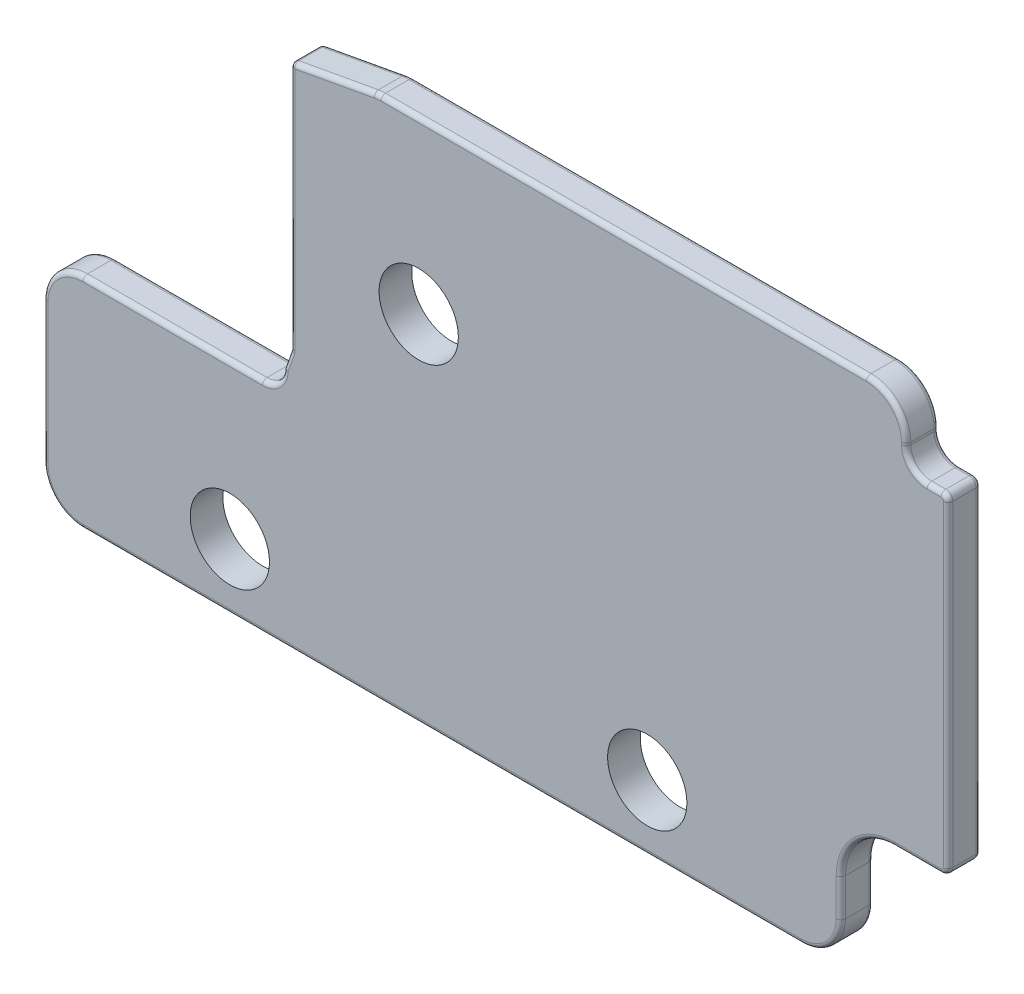
SolidWorks part; units mm, degrees
ref_plane "Front Plane" through (0, 0, 0) normal (0, 0, 1) x (1, 0, 0)
ref_plane "Top Plane" through (0, 0, 0) normal (0, 1, 0) x (1, 0, 0)
ref_plane "Right Plane" through (0, 0, 0) normal (1, 0, 0) x (0, 0, -1)
sketch "Sketch1" plane through (0, 0, 0) normal (0, 0, 1) x (1, 0, 0)
  line L13 (88.2, 306.15) -> (88.5, 306.9973)
  line L26 (88.5, 317.6667) -> (88.5, 306.9973)
  line L43 (87.3, 305.25) -> (79.6, 305.25)
  line L44 (77.9, 303.55) -> (77.9, 297.55)
  line L45 (79.6, 295.85) -> (110.4, 295.85)
  line L46 (112.1, 297.55) -> (112.1, 299.15)
  line L47 (114.4, 301.45) -> (116.4, 301.45)
  line L48 (116.7, 301.75) -> (116.7, 315.35)
  line L49 (116.4, 315.65) -> (115.8, 315.65)
  line L50 (114.9, 316.55) -> (114.9, 316.65)
  line L51 (113.2, 318.35) -> (92.3818, 318.35)
  line L52 (92.0753, 318.3221) -> (88.5, 317.6667)
  circle A2 centre (85.9, 298.65) radius 1.7
  circle A4 centre (103.8, 298.65) radius 1.7
  circle A6 centre (94, 311.05) radius 1.7
  arc A46 (87.3, 305.25) -> (88.2, 306.15) centre (87.3, 306.15) ccw
  arc A47 (79.6, 305.25) -> (77.9, 303.55) centre (79.6, 303.55) ccw
  arc A48 (77.9, 297.55) -> (79.6, 295.85) centre (79.6, 297.55) ccw
  arc A49 (110.4, 295.85) -> (112.1, 297.55) centre (110.4, 297.55) ccw
  arc A50 (114.4, 301.45) -> (112.1, 299.15) centre (114.4, 299.15) ccw
  arc A51 (116.4, 301.45) -> (116.7, 301.75) centre (116.4, 301.75) ccw
  arc A52 (116.7, 315.35) -> (116.4, 315.65) centre (116.4, 315.35) ccw
  arc A53 (114.9, 316.55) -> (115.8, 315.65) centre (115.8, 316.55) ccw
  arc A54 (114.9, 316.65) -> (113.2, 318.35) centre (113.2, 316.65) ccw
  arc A55 (92.3818, 318.35) -> (92.0753, 318.3221) centre (92.3818, 316.65) ccw
extrude "Boss-Extrude1" add sketch "Sketch1" along normal blind 1.4
fillet "Fillet1" radius 0.2 46 edges at (88.35, 306.5737, 1.4) (88.35, 306.5737, 0) (87.9364, 305.5136, 1.4) (83.45, 305.25, 1.4) (78.3979, 304.7521, 1.4) (77.9, 300.55, 1.4) (78.3979, 296.3479, 1.4) (95, 295.85, 1.4) (111.6021, 296.3479, 1.4) (112.1, 298.35, 1.4) (112.7737, 300.7763, 1.4) (115.4, 301.45, 1.4) (116.6121, 301.5379, 1.4) (116.7, 308.55, 1.4) (116.6121, 315.5621, 1.4) (116.1, 315.65, 1.4) (115.1636, 315.9136, 1.4) (114.9, 316.6, 1.4) (114.4021, 317.8521, 1.4) (90.2876, 317.9944, 1.4) (92.2279, 318.343, 1.4) (87.9364, 305.5136, 0) (83.45, 305.25, 0) (78.3979, 304.7521, 0) (77.9, 300.55, 0) (78.3979, 296.3479, 0) (95, 295.85, 0) (111.6021, 296.3479, 0) (112.1, 298.35, 0) (112.7737, 300.7763, 0) (115.4, 301.45, 0) (116.6121, 301.5379, 0) (116.7, 308.55, 0) (116.6121, 315.5621, 0) (116.1, 315.65, 0) (115.1636, 315.9136, 0) (114.9, 316.6, 0) (114.4021, 317.8521, 0) (90.2876, 317.9944, 0) (92.2279, 318.343, 0) (88.5, 317.6667, 0.7) (88.5, 312.332, 1.4) (88.5, 306.9973, 0.7) (88.5, 312.332, 0) (102.7909, 318.35, 1.4) (102.7909, 318.35, 0)
